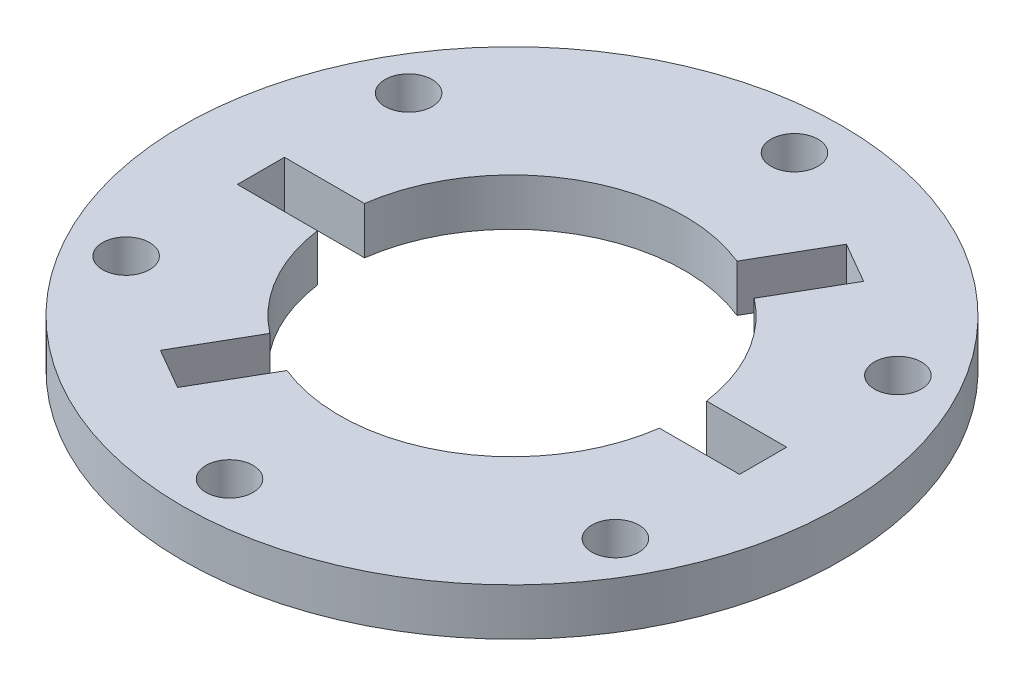
SolidWorks part; units mm, degrees
material "Chipboard"
ref_plane "Front Plane" through (0, 0, 0) normal (0, 0, 1) x (1, 0, 0)
ref_plane "Top Plane" through (0, 0, 0) normal (0, 1, 0) x (1, 0, 0)
ref_plane "Right Plane" through (0, 0, 0) normal (1, 0, 0) x (0, 0, -1)
sketch "Sketch1" plane through (0, 0, 0) normal (0, 1, 0) x (1, 0, 0)
  line L0 (0, 0) -> (-29.2038, 0) construction
  line L1 (0, 0) -> (-16.9821, -29.4138) construction
  line L2 (-10.8972, 1.5) -> (-16, 1.5)
  line L3 (-10.8972, -1.5) -> (-16, -1.5)
  line L4 (0, 27.361) -> (0, -29.4138) construction
  line L5 (-4.1496, -10.1873) -> (-6.701, -14.6064)
  line L6 (-6.701, -14.6064) -> (-9.299, -13.1064)
  line L7 (0, 0) -> (25.2436, 0) construction
  line L8 (0, 0) -> (15.2523, 26.4177) construction
  line L10 (1.299, -0.75) -> (-15.683, -30.1638) construction
  line L11 (-16, -1.5) -> (-16, 1.5)
  line L12 (-6.7477, -8.6873) -> (-9.299, -13.1064)
  line L13 (10.8972, -1.5) -> (16, -1.5)
  line L14 (10.8972, 1.5) -> (16, 1.5)
  line L15 (16, 1.5) -> (16, -1.5)
  line L16 (4.1496, 10.1873) -> (6.701, 14.6064)
  line L17 (6.701, 14.6064) -> (9.299, 13.1064)
  line L18 (6.7477, 8.6873) -> (9.299, 13.1064)
  circle A0 centre (0, 0) radius 21
  circle A1 centre (0, 0) radius 18 construction
  circle A2 centre (0, 18) radius 1.5
  circle A3 centre (15.5885, 9) radius 1.5
  circle A4 centre (15.5885, -9) radius 1.5
  circle A5 centre (0, -18) radius 1.5
  circle A6 centre (-15.5885, -9) radius 1.5
  circle A7 centre (-15.5885, 9) radius 1.5
  circle A8 centre (0, 0) radius 16 construction
  arc A9 (-10.8972, -1.5) -> (-6.7477, -8.6873) centre (0, 0) ccw
  arc A10 (-4.1496, -10.1873) -> (10.8972, -1.5) centre (0, 0) ccw
  arc A11 (10.8972, 1.5) -> (6.7477, 8.6873) centre (0, 0) ccw
  arc A12 (4.1496, 10.1873) -> (-10.8972, 1.5) centre (0, 0) ccw
  arc A13 (10.8972, 1.5) -> (10.8972, -1.5) centre (0, 0) cw construction
  point P6 (0, 1.5)
  point P18 (0, 0)
  point P20 (-29.2038, 1.5)
  point P21 (0, -1.5)
  point P22 (-29.2038, -1.5)
  point P23 (-0.866, 0.5)
  point P24 (-17.8481, -28.9138)
  point P49 (0, 0)
  dimension "D1" = 6
  dimension "D7" = 32
  dimension "D8" = 42
  dimension "D9" = 3
  dimension "D10" = 36
  dimension "D11" = 5
  dimension "D12" = 5
  dimension "D13" = 11
  dimension "D2" = 1.5
  dimension "D3" = 1.5
  dimension "D4" = 60
  dimension "D5" = 1.5
  dimension "D6" = 1.5
extrude "Boss-Extrude2" add sketch "Sketch1" along normal blind 3 contours A0 A12 L16 L17 L18 A11 L14 L15 L13 A10 L5 L6 L12 A9 L3 L11 L2 A7 A6 A5 A4 A3 A2
